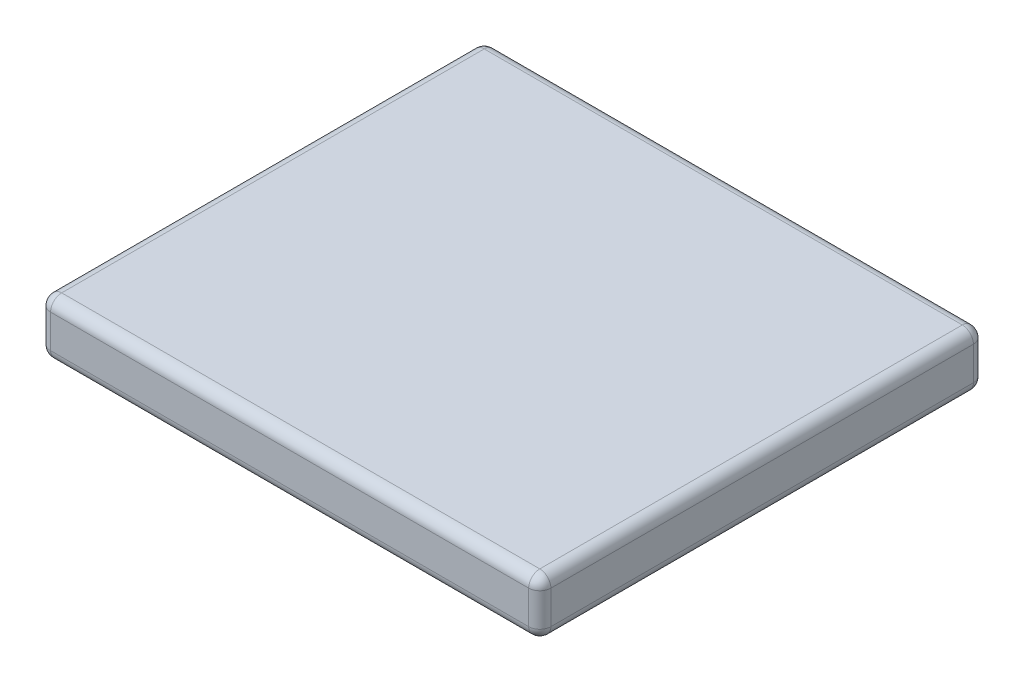
SolidWorks part; units mm, degrees
ref_plane "Front Plane" through (0, 0, 0) normal (0, 0, 1) x (1, 0, 0)
ref_plane "Top Plane" through (0, 0, 0) normal (0, 1, 0) x (1, 0, 0)
ref_plane "Right Plane" through (0, 0, 0) normal (1, 0, 0) x (0, 0, -1)
sketch "Sketch1" plane through (0, 0, 0) normal (0, 0, 1) x (1, 0, 0)
  line L1 (-45, 5) -> (45, 5)
  line L2 (-45, 5) -> (-45, -5)
  line L3 (-45, -5) -> (45, -5)
  line L4 (45, 5) -> (45, -5)
  line L5 (-45, 5) -> (45, -5) construction
  line L6 (-45, -5) -> (45, 5) construction
  point P0 (0, 0)
  dimension "D1" = 90
  dimension "D2" = 10
extrude "Boss-Extrude1" add sketch "Sketch1" along normal blind 80
fillet "Fillet1" radius 2 12 edges at (-45, 5, 40) (-45, -5, 40) (0, 5, 0) (-45, 0, 0) (0, -5, 0) (45, -5, 40) (45, 5, 40) (45, 0, 0) (0, -5, 80) (-45, 0, 80) (0, 5, 80) (45, 0, 80)
